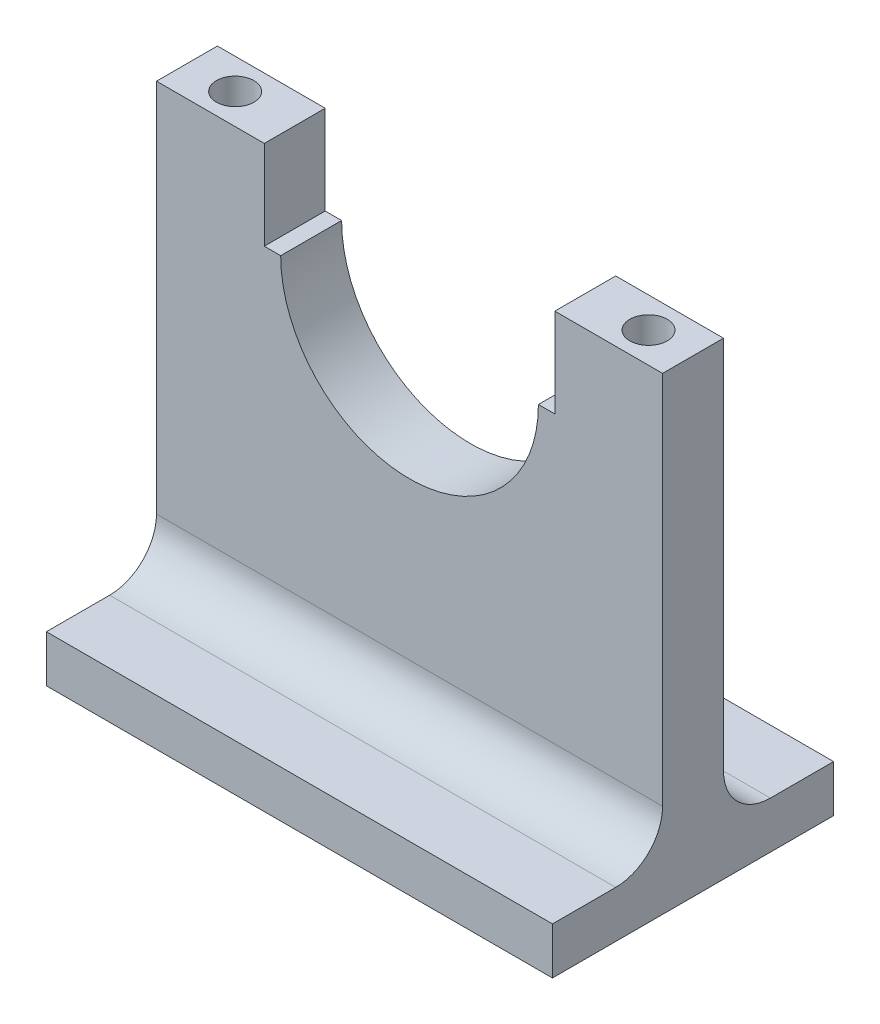
SolidWorks part; units mm, degrees
ref_plane "Front Plane" through (0, 0, 0) normal (0, 0, 1) x (1, 0, 0)
ref_plane "Top Plane" through (0, 0, 0) normal (0, 1, 0) x (1, 0, 0)
ref_plane "Right Plane" through (0, 0, 0) normal (1, 0, 0) x (0, 0, -1)
sketch "Sketch1" plane through (0, 0, 0) normal (0, 0, 1) x (1, 0, 0)
  line L1 (-54, -5) -> (54, -5)
  line L2 (-54, -5) -> (-54, 5)
  line L3 (-54, 5) -> (54, 5)
  line L4 (54, -5) -> (54, 5)
  dimension "D1" = 108
  dimension "D2" = 10
extrude "Boss-Extrude1" add sketch "Sketch1" along normal mid plane 60
sketch "Sketch2" plane through (0, 0, 0) normal (0, 0, 1) x (1, 0, 0)
  line L0 (-54, 5) -> (-54, 95)
  line L1 (-54, 95) -> (-31, 95)
  line L2 (-31, 95) -> (-31, 76)
  line L3 (-31, 76) -> (-27.5, 76)
  line L4 (54, 5) -> (-54, 5) construction
  line L5 (31, 76) -> (27.5, 76)
  line L6 (31, 95) -> (31, 76)
  line L7 (54, 95) -> (31, 95)
  line L8 (54, 5) -> (54, 95)
  line L9 (-54, 5) -> (54, 5)
  arc A0 (-27.5, 76) -> (27.5, 76) centre (0, 76) ccw
  point P7 (0, 5)
  dimension "D4" = 27.5
  dimension "D1" = 90
  dimension "D2" = 23
  dimension "D3" = 19
extrude "Boss-Extrude2" add sketch "Sketch2" along normal mid plane 13
sketch "Sketch3" plane through (0, 95, 0) normal (0, 1, 0) x (1, 0, 0)
  line L1 (54, -6.5) -> (54, 6.5) construction
  circle A0 centre (44.5, 0) radius 4
  circle A1 centre (-43.7155, 0) radius 4
  point P2 (0, 0)
  dimension "D1" = 9.5
extrude "Cut-Extrude1" cut sketch "Sketch3" against normal blind 22
fillet "Fillet1" radius 10 2 edges at (0, 5, 6.5) (0, 5, -6.5)
